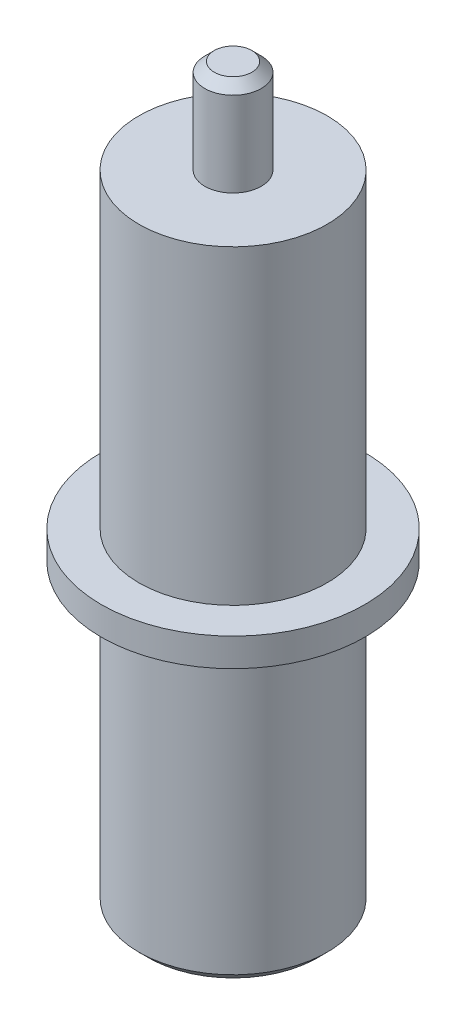
SolidWorks part; units mm, degrees
ref_plane "Спереди" through (0, 0, 0) normal (0, 0, 1) x (1, 0, 0)
ref_plane "Сверху" through (0, 0, 0) normal (0, 1, 0) x (1, 0, 0)
ref_plane "Справа" through (0, 0, 0) normal (1, 0, 0) x (0, 0, -1)
sketch "Эскиз1" plane through (0, 0, 0) normal (0, 0, 1) x (1, 0, 0)
  line L0 (-7, 16) -> (-7, 17.5)
  line L1 (-7, 17.5) -> (-5, 17.5)
  line L2 (-5, 17.5) -> (-5, 34)
  line L3 (-5, 34) -> (-1.5, 34)
  line L4 (-1.5, 34) -> (-1.5, 39)
  line L5 (-1.5, 39) -> (0, 39)
  line L6 (-7, 16) -> (-5, 16)
  line L7 (-5, 16) -> (-5, 0)
  line L8 (-5, 0) -> (0, 0)
  line L9 (0, 0) -> (0, 39)
  line L10 (0, 16.7147) -> (0, -4297.6648) construction
  line L11 (5.5, 16) -> (-5.5, 16) construction
  line L12 (-7.9, 17.5) -> (7.9, 17.5) construction
  line L13 (-1.5, 34.5) -> (1.5, 34.5) construction
  line L14 (-1.5, 34.5) -> (1.5, 34.5) construction
  point P19 (0, 0)
  dimension "D1" = 10
  dimension "D2" = 10
  dimension "D3" = 2
  dimension "D4" = 0.5
  dimension "D5" = 5
revolve "Повернуть1" add sketch "Эскиз1" angle 360 about L10
chamfer "Фаска1" distance 0.5 angle 45 2 edges at (0, 0, 5) (0, 39, 1.5)
